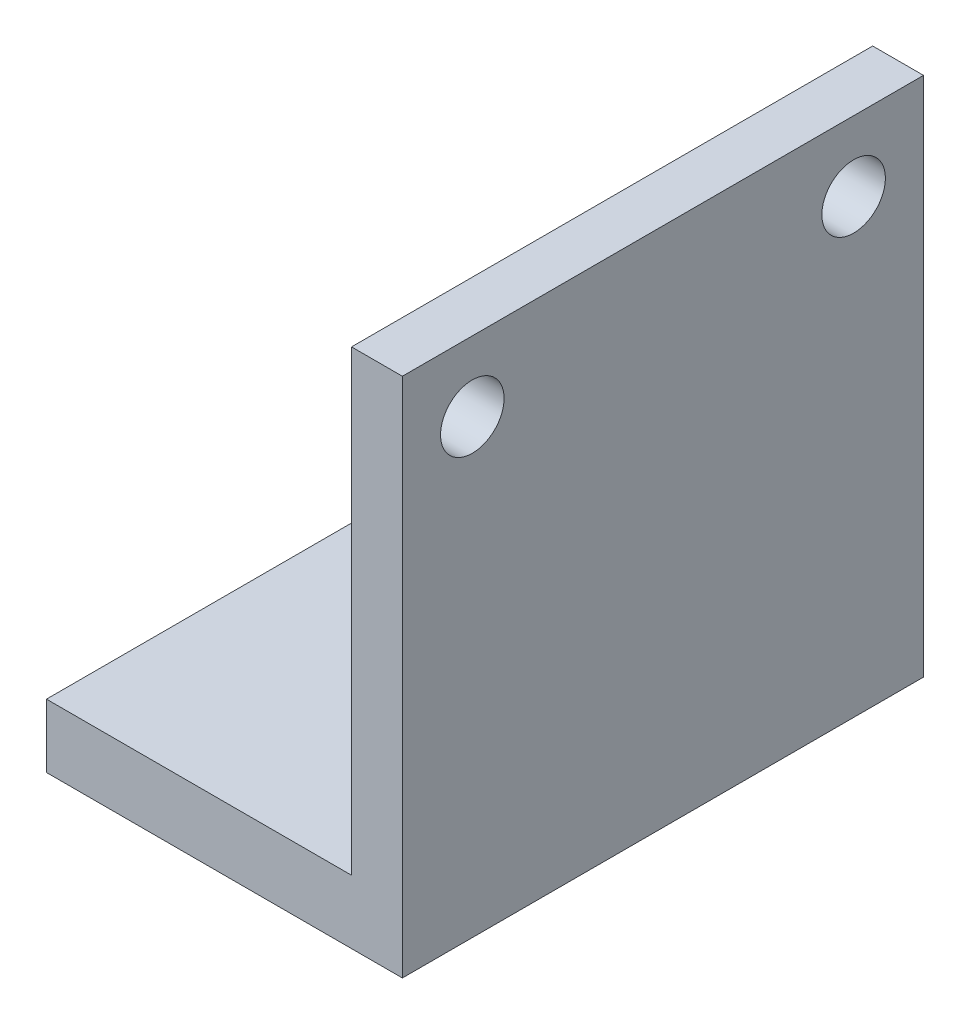
SolidWorks part; units mm, degrees
ref_plane "Ground" through (0, 0, 0) normal (0, 0, 1) x (1, 0, 0)
ref_plane "Right" through (0, 0, 0) normal (0, 1, 0) x (1, 0, 0)
ref_plane "Front" through (0, 0, 0) normal (1, 0, 0) x (0, 0, -1)
sketch "Sketch1" plane through (0, 0, 0) normal (1, 0, 0) x (0, 0, -1)
  line L0 (-7.5, 7.5) -> (7.5, 7.5) construction
  line L1 (-10.25, -10.25) -> (10.25, -10.25)
  line L2 (-10.25, -10.25) -> (-10.25, 10.25)
  line L3 (-10.25, 10.25) -> (10.25, 10.25)
  line L4 (10.25, -10.25) -> (10.25, 10.25)
  line L5 (-10.25, -10.25) -> (10.25, 10.25) construction
  line L6 (-10.25, 10.25) -> (10.25, -10.25) construction
  circle A0 centre (-7.5, 7.5) radius 1.25
  circle A1 centre (7.5, 7.5) radius 1.25
  point P0 (0, 0)
  point P10 (0, 7.5)
  point P11 (0, 10.25)
  dimension "D3" = 2.5
  dimension "D1" = 20.5
  dimension "D2" = 20.5
  dimension "D4" = 15
extrude "Boss-Extrude1" add sketch "Sketch1" along normal blind 2
sketch "Sketch2" plane through (0, 0, 0) normal (-1, 0, 0) x (0, 0, 1)
  line L1 (-10.25, -7.75) -> (10.25, -7.75)
  line L2 (-10.25, -7.75) -> (-10.25, -10.25)
  line L3 (-10.25, -10.25) -> (10.25, -10.25)
  line L4 (-10.25, 10.25) -> (-10.25, -10.25)
  line L5 (-10.25, -10.25) -> (10.25, -10.25)
  line L6 (10.25, -10.25) -> (10.25, 10.25)
  line L7 (10.25, 10.25) -> (-10.25, 10.25)
  line L8 (-10.25, 10.25) -> (-10.25, -10.25)
  line L9 (-10.25, -10.25) -> (10.25, -10.25)
  line L10 (10.25, -10.25) -> (10.25, 10.25)
  line L11 (10.25, 10.25) -> (-10.25, 10.25)
  line L12 (10.25, -7.75) -> (10.25, -10.25)
  line M10 (-10.25, 10.25) -> (-10.25, -10.25)
  line M11 (-10.25, -10.25) -> (10.25, -10.25)
  line M12 (10.25, -10.25) -> (10.25, 10.25)
  dimension "D2" = 2.5
  dimension "D1" = 0
extrude "Boss-Extrude2" add sketch "Sketch2" along normal blind 12 contours L1 M10 M11 M12
